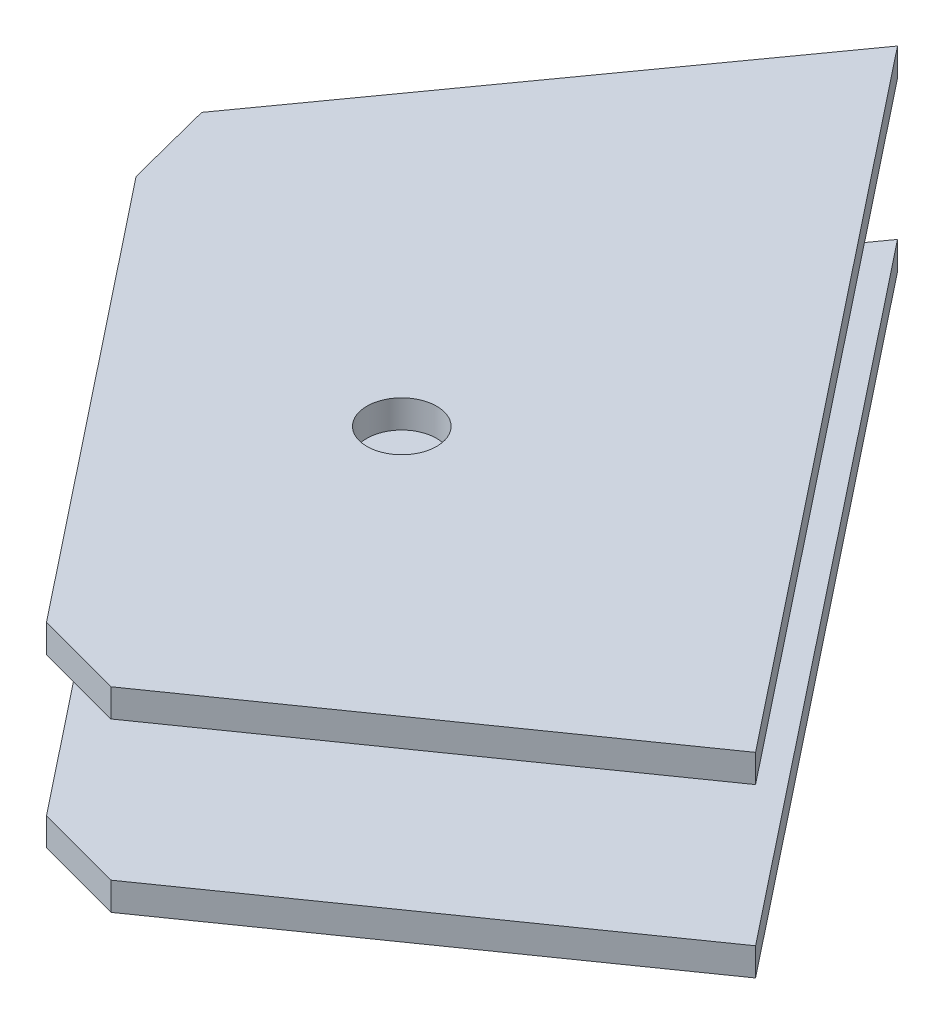
SolidWorks part; units mm, degrees
material "Plain Carbon Steel"
ref_plane "Front Plane" through (0, 0, 0) normal (0, 0, 1) x (1, 0, 0)
ref_plane "Top Plane" through (0, 0, 0) normal (0, 1, 0) x (1, 0, 0)
ref_plane "Right Plane" through (0, 0, 0) normal (1, 0, 0) x (0, 0, -1)
sketch "Sketch1" plane through (0, 0, 0) normal (0, 1, 0) x (1, 0, 0)
  line L0 (-31.7774, 7.6035) -> (-3.3105, 47.3435)
  line L2 (-3.3105, 47.3435) -> (37.8448, -4.6144)
  line L4 (37.8448, -4.6144) -> (-0.714, -31.6136)
  line L5 (-0.714, -31.6136) -> (-31.7774, 7.6035)
  line L6 (242.7216, 138.8419) -> (-0.714, -31.6136) construction
  circle A1 centre (0, 0) radius 6.35
ref_plane "Plane1" through (0, 6.35, 0) normal (0, 1, 0) x (-1, 0, 0)
ref_plane "Plane2" through (0, -6.35, 0) normal (0, 1, 0) x (-1, 0, 0)
sketch "Sketch2" plane through (0, 6.35, 0) normal (0, 1, 0) x (-1, 0, 0)
  line L4 (0.714, 31.6136) -> (31.7774, -7.6035) construction
  line L5 (-41.7944, 9.6008) -> (7.4122, -52.5219) construction
  line L11 (0.714, 31.6136) -> (31.7774, -7.6035)
  line L12 (-41.7944, 9.6008) -> (7.4122, -52.5219)
  line L13 (-7.2929, 33.759) -> (0.714, 31.6136)
  line L14 (33.8368, -15.633) -> (31.7774, -7.6035)
  line L15 (-47.0051, 5.9522) -> (3.5653, -57.8922)
  line L16 (3.5653, -57.8922) -> (39.726, -7.4116)
  line L17 (39.726, -7.4116) -> (1.9751, 40.2485)
  line L18 (1.9751, 40.2485) -> (-47.0051, 5.9522)
  line L20 (7.4122, -52.5219) -> (33.8368, -15.633)
  line L22 (-7.2929, 33.759) -> (-41.7944, 9.6008)
  circle A0 centre (0, 0) radius 3.175
  dimension "D1" = 6.35
extrude "Boss-Extrude2" add sketch "Sketch2" along normal blind 2.54 separate body
sketch "Sketch4" plane through (0, -6.35, 0) normal (0, 1, 0) x (-1, 0, 0)
  line L0 (0.714, 31.6136) -> (31.7774, -7.6035) construction
  line L1 (33.8368, -15.633) -> (31.7774, -7.6035) construction
  line L2 (7.4122, -52.5219) -> (33.8368, -15.633) construction
  line L3 (-41.7944, 9.6008) -> (7.4122, -52.5219) construction
  line L4 (-7.2929, 33.759) -> (-41.7944, 9.6008) construction
  line L5 (-7.2929, 33.759) -> (0.714, 31.6136) construction
  line L6 (0.714, 31.6136) -> (31.7774, -7.6035)
  line L7 (33.8368, -15.633) -> (31.7774, -7.6035)
  line L8 (7.4122, -52.5219) -> (33.8368, -15.633)
  line L9 (-41.7944, 9.6008) -> (7.4122, -52.5219)
  line L10 (-7.2929, 33.759) -> (-41.7944, 9.6008)
  line L11 (-7.2929, 33.759) -> (0.714, 31.6136)
  circle A1 centre (0, 0) radius 3.175
extrude "Boss-Extrude3" add sketch "Sketch4" against normal blind 2.54 separate body
sketch "Sketch5" plane through (0, -8.89, 0) normal (0, -1, 0) x (1, 0, 0)
  circle A0 centre (-4.3509, 7.8543) radius 1.1303
  circle A1 centre (-9.8266, 0.0922) radius 1.1303
  circle A2 centre (-7.1681, -4.6791) radius 1.1303
extrude "Cut-Extrude1" cut sketch "Sketch5" against normal blind 5.08
